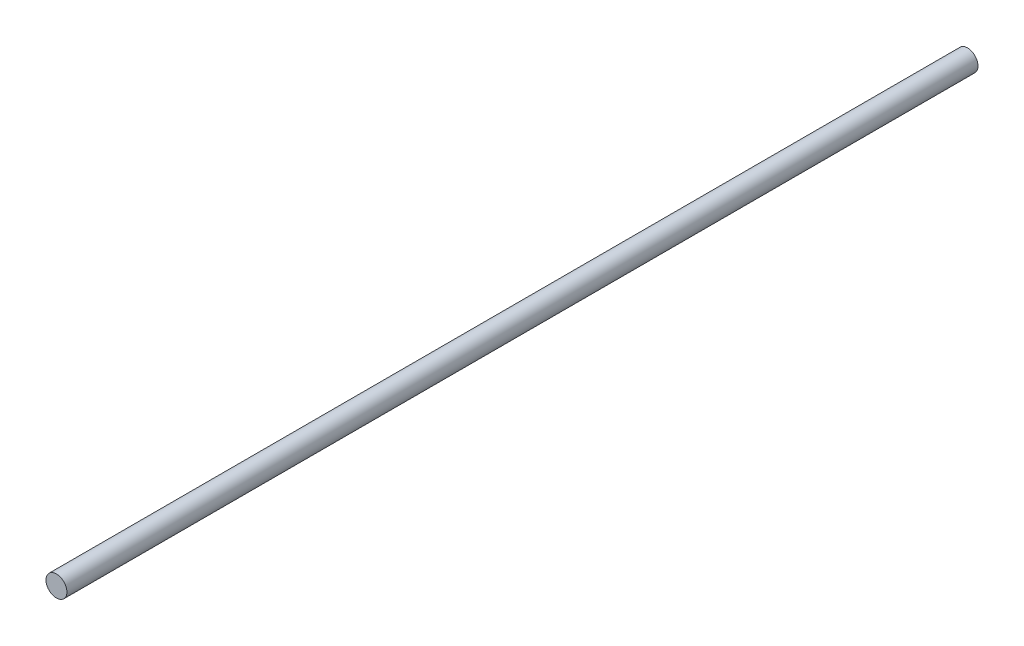
SolidWorks part; units mm, degrees
material "Plain Carbon Steel"
ref_plane "Front Plane" through (0, 0, 0) normal (0, 0, 1) x (1, 0, 0)
ref_plane "Top Plane" through (0, 0, 0) normal (0, 1, 0) x (1, 0, 0)
ref_plane "Right Plane" through (0, 0, 0) normal (1, 0, 0) x (0, 0, -1)
sketch "Sketch1" plane through (0, 0, 0) normal (0, 0, 1) x (1, 0, 0)
  circle A0 centre (0, 0) radius 6
  dimension "D1" = 12
extrude "Boss-Extrude2" add sketch "Sketch1" along normal mid plane 522.5
